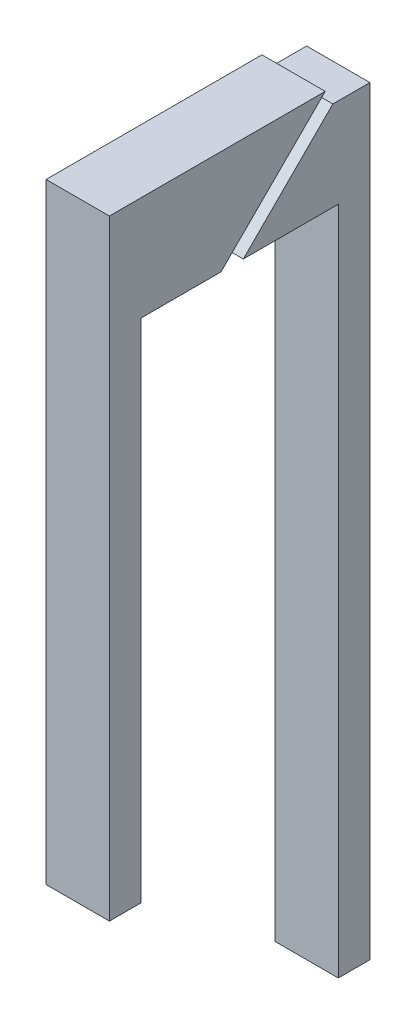
SolidWorks part; units mm, degrees
material "Chrome Stainless Steel"
ref_plane "Front Plane" through (0, 0, 0) normal (0, 0, 1) x (1, 0, 0)
ref_plane "Top Plane" through (0, 0, 0) normal (0, 1, 0) x (1, 0, 0)
ref_plane "Right Plane" through (0, 0, 0) normal (1, 0, 0) x (0, 0, -1)
sketch "Sketch2" plane through (0, 0, 0) normal (1, 0, 0) x (0, 0, -1)
  line L0 (24.2041, -32.7033) -> (22.7898, -34.1175)
  line L1 (24.2898, -34.1175) -> (24.2898, -44.7033)
  line L2 (24.2898, -44.7033) -> (24.7898, -44.7033)
  line L3 (24.7898, -44.7033) -> (24.7898, -32.7033)
  line L4 (24.7898, -32.7033) -> (24.2041, -32.7033)
  line L5 (22.7898, -34.1175) -> (24.2898, -34.1175)
  line L6 (24.0837, -32.4711) -> (22.4373, -34.1175)
  line L7 (22.4373, -34.1175) -> (21.1744, -34.1175)
  line L8 (21.1744, -34.1175) -> (21.1744, -42.1175)
  line L9 (21.1744, -42.1175) -> (20.6744, -42.1175)
  line L10 (20.6744, -42.1175) -> (20.6744, -32.4711)
  line L11 (20.6744, -32.4711) -> (24.0837, -32.4711)
extrude "Boss-Extrude1" add sketch "Sketch2" along normal blind 1
